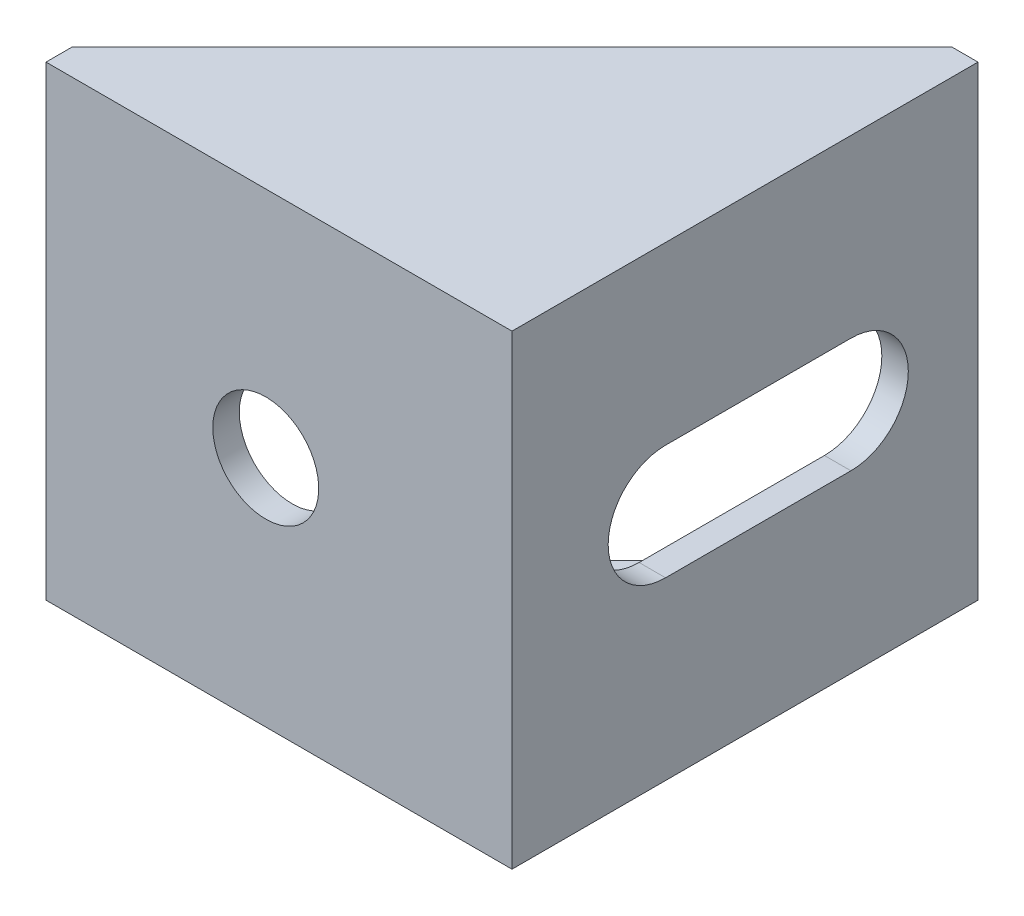
SolidWorks part; units mm, degrees
ref_plane "Front Plane" through (0, 0, 0) normal (0, 0, 1) x (1, 0, 0)
ref_plane "Top Plane" through (0, 0, 0) normal (0, 1, 0) x (1, 0, 0)
ref_plane "Right Plane" through (0, 0, 0) normal (1, 0, 0) x (0, 0, -1)
sketch "Sketch1" plane through (0, 0, 0) normal (0, 1, 0) x (1, 0, 0)
  line L0 (-27.94, 1.5875) -> (-1.5875, 1.5875)
  line L1 (0, 0) -> (-3.3354, 0)
  line L2 (0, 0) -> (0, 27.94)
  line L3 (0, 27.94) -> (-1.5875, 27.94)
  line L5 (0, 0) -> (-27.94, 0)
  line L6 (0, 0) -> (0, 2.8222)
  line L8 (-27.94, 0) -> (-27.94, 1.5875)
  line L9 (-1.5875, 1.5875) -> (-1.5875, 27.94)
  dimension "D1" = 27.94
  dimension "D2" = 1.5875
extrude "Boss-Extrude1" add sketch "Sketch1" along normal blind 25.4 contours L5 L8 L0 L9 L3 L2
sketch "Sketch2" plane through (0, 25.4, 0) normal (0, 1, 0) x (1, 0, 0)
  line L0 (-1.5875, 27.94) -> (-27.94, 1.5875)
  line L1 (-27.94, 1.5875) -> (-27.94, 0)
  line L2 (-27.94, 0) -> (0, 0)
  line L3 (0, 0) -> (0, 27.94)
  line L4 (0, 27.94) -> (-1.5875, 27.94)
extrude "Boss-Extrude2" add sketch "Sketch2" along normal blind 1.27
sketch "Sketch3" plane through (0, 0, 0) normal (0, -1, 0) x (1, 0, 0)
  line L0 (-27.94, -1.5875) -> (-1.5875, -27.94)
  line L1 (-1.5875, -27.94) -> (0, -27.94)
  line L2 (0, -27.94) -> (0, 0)
  line L3 (0, 0) -> (-27.94, 0)
  line L4 (-27.94, 0) -> (-27.94, -1.5875)
extrude "Boss-Extrude3" add sketch "Sketch3" along normal blind 1.27
sketch "Sketch4" plane through (-1.5875, 0, 0) normal (-1, 0, 0) x (0, 0, 1)
  line L0 (-27.94, 12.7) -> (-1.5875, 12.7) construction
  line L1 (-27.94, 25.4) -> (-27.94, 0) construction
  line L2 (-1.5875, 25.4) -> (-1.5875, 0) construction
  line L3 (-20.32, 9.2583) -> (-9.2075, 9.2583)
  line L4 (-20.32, 16.1417) -> (-9.2075, 16.1417)
  arc A0 (-20.32, 9.2583) -> (-20.32, 16.1417) centre (-20.32, 12.7) cw
  arc A1 (-9.2075, 9.2583) -> (-9.2075, 16.1417) centre (-9.2075, 12.7) ccw
  point P9 (-23.7617, 12.7)
  point P13 (-15.4066, 9.2583)
  dimension "D1" = 3.4417
  dimension "D2" = 7.62
  dimension "D3" = 7.62
extrude "Cut-Extrude1" cut sketch "Sketch4" against normal through all
sketch "Sketch5" plane through (0, 0, -1.5875) normal (0, 0, -1) x (-1, 0, 0)
  line L0 (1.5875, 12.7) -> (27.94, 12.7) construction
  line L1 (1.5875, 25.4) -> (1.5875, 0) construction
  line L2 (27.94, 25.4) -> (27.94, 0) construction
  line L3 (14.7638, 25.4) -> (14.7638, 0) construction
  line L4 (27.94, 25.4) -> (1.5875, 25.4) construction
  line L5 (27.94, 0) -> (1.5875, 0) construction
  circle A0 centre (14.7638, 12.7) radius 3.175
  dimension "D1" = 6.35
extrude "Cut-Extrude2" cut sketch "Sketch5" against normal through all
